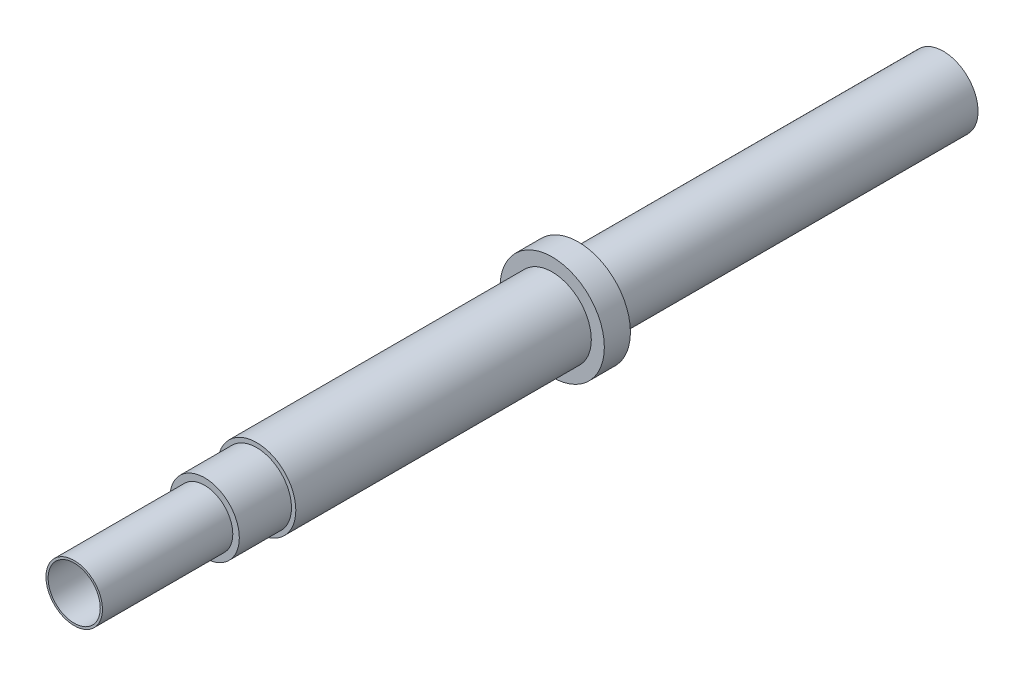
SolidWorks part; units mm, degrees
ref_plane "Front Plane" through (0, 0, 0) normal (0, 0, 1) x (1, 0, 0)
ref_plane "Top Plane" through (0, 0, 0) normal (0, 1, 0) x (1, 0, 0)
ref_plane "Right Plane" through (0, 0, 0) normal (1, 0, 0) x (0, 0, -1)
sketch "Sketch2" plane through (0, 0, 0) normal (0, 0, 1) x (1, 0, 0)
  circle A0 centre (0, 0) radius 4
  circle A1 centre (0, 0) radius 3
extrude "Boss-Extrude1" add sketch "Sketch2" along normal blind 42
sketch "Sketch3" plane through (0, 0, 42) normal (0, 0, 1) x (1, 0, 0)
  circle A0 centre (0, 0) radius 6
  circle A1 centre (0, 0) radius 4
extrude "Boss-Extrude2" add sketch "Sketch3" along normal blind 3 separate body
sketch "Sketch4" plane through (0, 0, 45) normal (0, 0, 1) x (1, 0, 0)
  circle A1 centre (0, 0) radius 4
  circle A2 centre (0, 0) radius 4.5
extrude "Boss-Extrude3" add sketch "Sketch4" along normal blind 34
sketch "Sketch5" plane through (0, 0, 79) normal (0, 0, 1) x (1, 0, 0)
  circle A0 centre (0, 0) radius 3
  circle A1 centre (0, 0) radius 4
extrude "Boss-Extrude4" add sketch "Sketch5" along normal blind 6 separate body
sketch "Sketch6" plane through (0, 0, 85) normal (0, 0, 1) x (1, 0, 0)
  circle A0 centre (0, 0) radius 3
  circle A1 centre (0, 0) radius 3.25
extrude "Boss-Extrude5" add sketch "Sketch6" along normal blind 15
